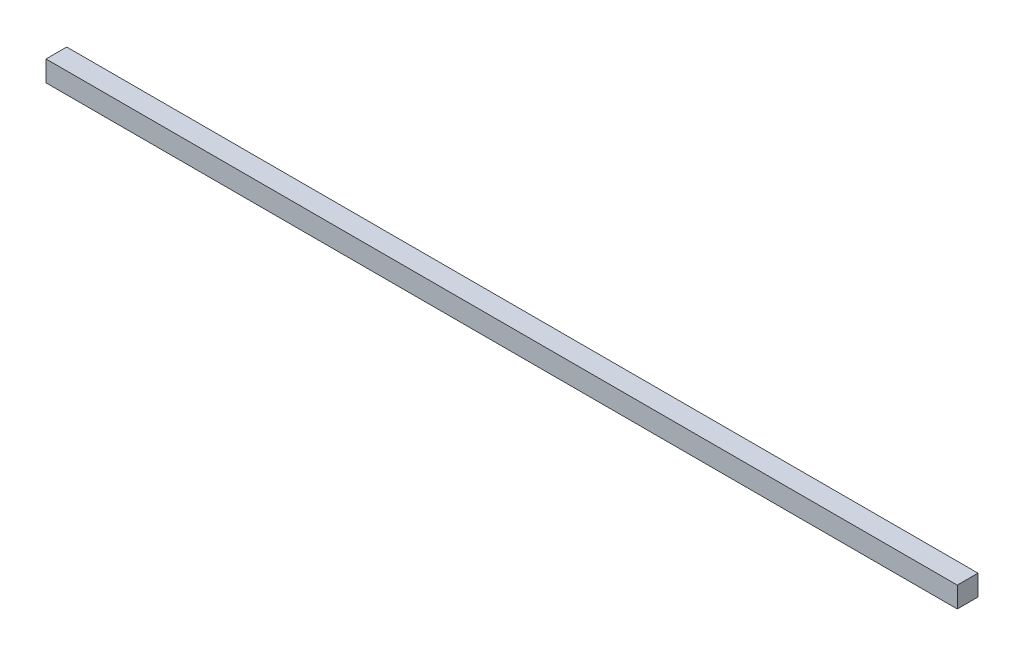
SolidWorks part; units mm, degrees
ref_plane "Front Plane" through (0, 0, 0) normal (0, 0, 1) x (1, 0, 0)
ref_plane "Top Plane" through (0, 0, 0) normal (0, 1, 0) x (1, 0, 0)
ref_plane "Right Plane" through (0, 0, 0) normal (1, 0, 0) x (0, 0, -1)
sketch "Sketch1" plane through (0, 0, 0) normal (0, 0, 1) x (1, 0, 0)
  line L1 (0, 0) -> (132, 0)
  line L2 (0, 0) -> (0, 3)
  line L3 (0, 3) -> (132, 3)
  line L4 (132, 0) -> (132, 3)
  dimension "D1" = 132
  dimension "D2" = 3
extrude "Profile" add sketch "Sketch1" along normal blind 3
equation "\"Profile_Depth\"= 3mm"
equation "\"D1@Profile\" = \"Profile_Depth\""
equation "\"Profile_Sketch_1\"= 132mm"
equation "\"D1@Sketch1\" = \"Profile_Sketch_1\""
equation "\"Profile_Sketch_2\"= 3mm"
equation "\"D2@Sketch1\" = \"Profile_Sketch_2\""
equation "\"EnvelopeWidth\"= 132mm"
equation "\"EnvelopeHeight\"= 3mm"
